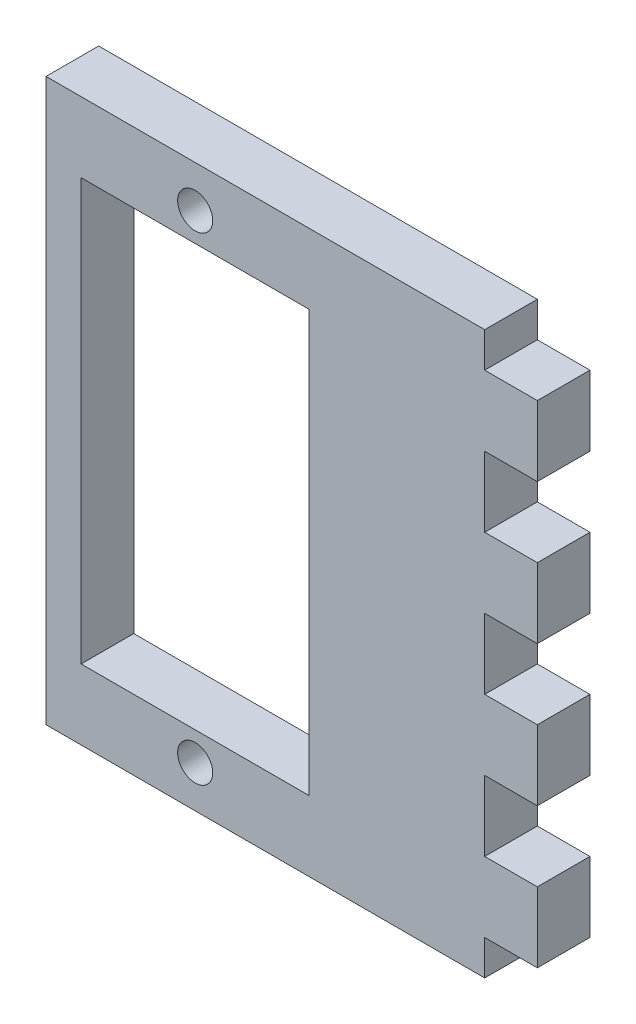
SolidWorks part; units mm, degrees
ref_plane "Front Plane" through (0, 0, 0) normal (0, 0, 1) x (1, 0, 0)
ref_plane "Top Plane" through (0, 0, 0) normal (0, 1, 0) x (1, 0, 0)
ref_plane "Right Plane" through (0, 0, 0) normal (1, 0, 0) x (0, 0, -1)
sketch "Sketch1" plane through (0, 0, 0) normal (0, 0, 1) x (1, 0, 0)
  line L0 (16.5, 14) -> (19.5, 14)
  line L1 (-8.5, -16) -> (16.5, -16)
  line L2 (-8.5, -16) -> (-8.5, 16)
  line L3 (-8.5, 16) -> (16.5, 16)
  line L4 (16.5, -16) -> (16.5, -14)
  line L7 (19.5, 14) -> (19.5, 10)
  line L8 (19.5, 10) -> (16.5, 10)
  line L9 (16.5, 6) -> (19.5, 6)
  line L10 (19.5, 6) -> (19.5, 2)
  line L11 (19.5, 2) -> (16.5, 2)
  line L12 (16.5, -14) -> (19.5, -14)
  line L13 (19.5, -14) -> (19.5, -10)
  line L14 (19.5, -10) -> (16.5, -10)
  line L15 (16.5, -6) -> (19.5, -6)
  line L16 (19.5, -6) -> (19.5, -2)
  line L17 (19.5, -2) -> (16.5, -2)
  line L18 (16.5, 14) -> (16.5, 16)
  line L19 (16.5, 6) -> (16.5, 10)
  line L20 (16.5, -2) -> (16.5, 2)
  line L21 (16.5, -10) -> (16.5, -6)
  line L22 (0, 0) -> (6.5, 0) construction
  line L23 (6.5, -12) -> (-6.5, -12)
  line L24 (6.5, -12) -> (6.5, 12)
  line L25 (6.5, 12) -> (-6.5, 12)
  line L26 (-6.5, -12) -> (-6.5, 12)
  line L27 (6.5, -12) -> (-6.5, 12) construction
  line L28 (6.5, 12) -> (-6.5, -12) construction
  circle A0 centre (0, 13.625) radius 1
  circle A1 centre (0, -13.625) radius 1
  point P0 (0, 0)
  point P20 (0, 0)
  point P33 (16.5, 0)
  point P34 (-8.5, 0)
  dimension "D5" = 2
  dimension "D1" = 32
  dimension "D2" = 4
  dimension "D3" = 24
  dimension "D4" = 13.625
  dimension "D6" = 13
  dimension "D7" = 25
  dimension "D8" = 3
  dimension "D9" = 4
  dimension "D10" = 2
extrude "Boss-Extrude1" add sketch "Sketch1" along normal blind 3
